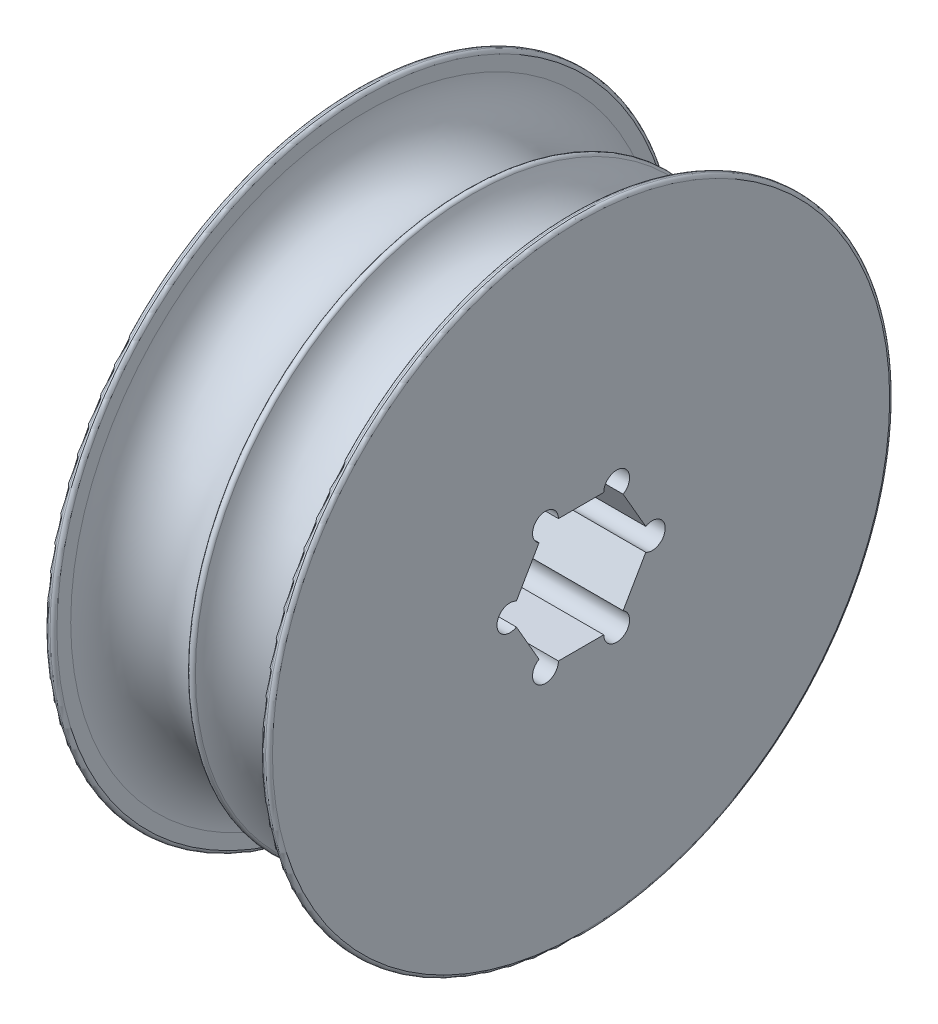
SolidWorks part; units mm, degrees
ref_plane "Front Plane" through (0, 0, 0) normal (0, 0, 1) x (1, 0, 0)
ref_plane "Top Plane" through (0, 0, 0) normal (0, 1, 0) x (1, 0, 0)
ref_plane "Right Plane" through (0, 0, 0) normal (1, 0, 0) x (0, 0, -1)
sketch "Sketch1" plane through (0, 0, 0) normal (0, 1, 0) x (1, 0, 0)
  line L0 (-13, 0) -> (0, 0)
  line L4 (0, 0) -> (0, 18.1)
  line L5 (0, 18.1) -> (-0.5, 18.1)
  line L6 (-0.5, 18.1) -> (-0.5, 17.1)
  line L7 (-6.5, 17.1) -> (-6.5, 0) construction
  line L8 (-12.5, 18.1) -> (-12.5, 17.1)
  line L9 (-13, 18.1) -> (-12.5, 18.1)
  line L10 (-13, 0) -> (-13, 18.1)
  arc A2 (-6.5, 17.1) -> (-0.5, 17.1) centre (-3.5, 17.1) ccw
  arc A3 (-6.5, 17.1) -> (-12.5, 17.1) centre (-9.5, 17.1) cw
  arc A4 (-0.5, 17.1) -> (-6.5, 17.1) centre (-3.5, 17.1) ccw construction
  point P9 (-3.5, 20.1)
  point P17 (-9.5, 20.1)
  dimension "D1" = 6
  dimension "D2" = 20.1
  dimension "D3" = 13
  dimension "D4" = 1
revolve "Revolve1" add sketch "Sketch1" angle 360 about L0
sketch "Sketch2" plane through (0, 0, 0) normal (1, 0, 0) x (0, 0, -1)
  line L0 (-1.314, 3.575) -> (1.314, 3.575)
  line L2 (2.439, 2.9255) -> (3.7531, 0.6495)
  line L3 (3.7531, -0.6495) -> (2.439, -2.9255)
  line L4 (1.314, -3.575) -> (-1.314, -3.575)
  line L5 (-2.439, -2.9255) -> (-3.7531, -0.6495)
  line L6 (-3.7531, 0.6495) -> (-2.439, 2.9255)
  arc A1 (2.439, 2.9255) -> (1.314, 3.575) centre (2.064, 3.575) ccw
  arc A2 (3.7531, -0.6495) -> (3.7531, 0.6495) centre (4.1281, 0) ccw
  arc A3 (1.314, -3.575) -> (2.439, -2.9255) centre (2.064, -3.575) ccw
  arc A4 (-2.439, -2.9255) -> (-1.314, -3.575) centre (-2.064, -3.575) ccw
  arc A5 (-3.7531, 0.6495) -> (-3.7531, -0.6495) centre (-4.1281, 0) ccw
  arc A6 (-1.314, 3.575) -> (-2.439, 2.9255) centre (-2.064, 3.575) ccw
  point P3 (0, 0)
  point P4 (2.8244, 4.2008)
  point P5 (0, 0)
  point P16 (-4.4362, -0.4001)
  point P20 (0, 0)
  point P23 (0, 0)
  dimension "D1" = 6
  dimension "D3" = 1.5
  dimension "D2" = 7.15
extrude "Cut-Extrude1" cut sketch "Sketch2" against normal through all both and the other way through all
fillet "Fillet1" radius 0.2 5 edges at (-6.5, 0, 17.1) (0, 0, 18.1) (-0.5, 0, 18.1) (-12.5, 0, 18.1) (-13, 0, 18.1)
